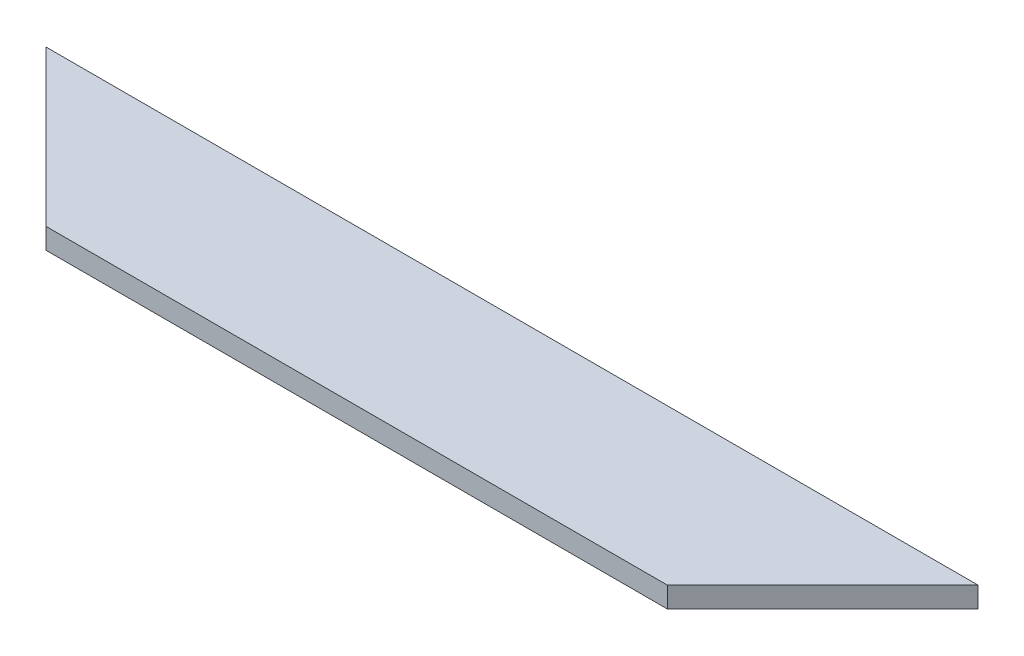
SolidWorks part; units mm, degrees
material "1060 Сплав"
ref_plane "Front" through (0, 0, 0) normal (0, 0, 1) x (1, 0, 0)
ref_plane "Top" through (0, 0, 0) normal (0, 1, 0) x (1, 0, 0)
ref_plane "Right" through (0, 0, 0) normal (1, 0, 0) x (0, 0, -1)
sketch "Эскиз1" plane through (0, 0, 0) normal (0, 1, 0) x (1, 0, 0)
  line L0 (0, 15) -> (15, 0)
  line L1 (15, 0) -> (75, 0)
  line L3 (0, 15) -> (90, 15)
  line L5 (90, 15) -> (75, 0)
  dimension "D1" = 15
  dimension "D2" = 45
  dimension "D3" = 45
  dimension "D4" = 90
extrude "Бобышка-Вытянуть1" add sketch "Эскиз1" along normal blind 2
